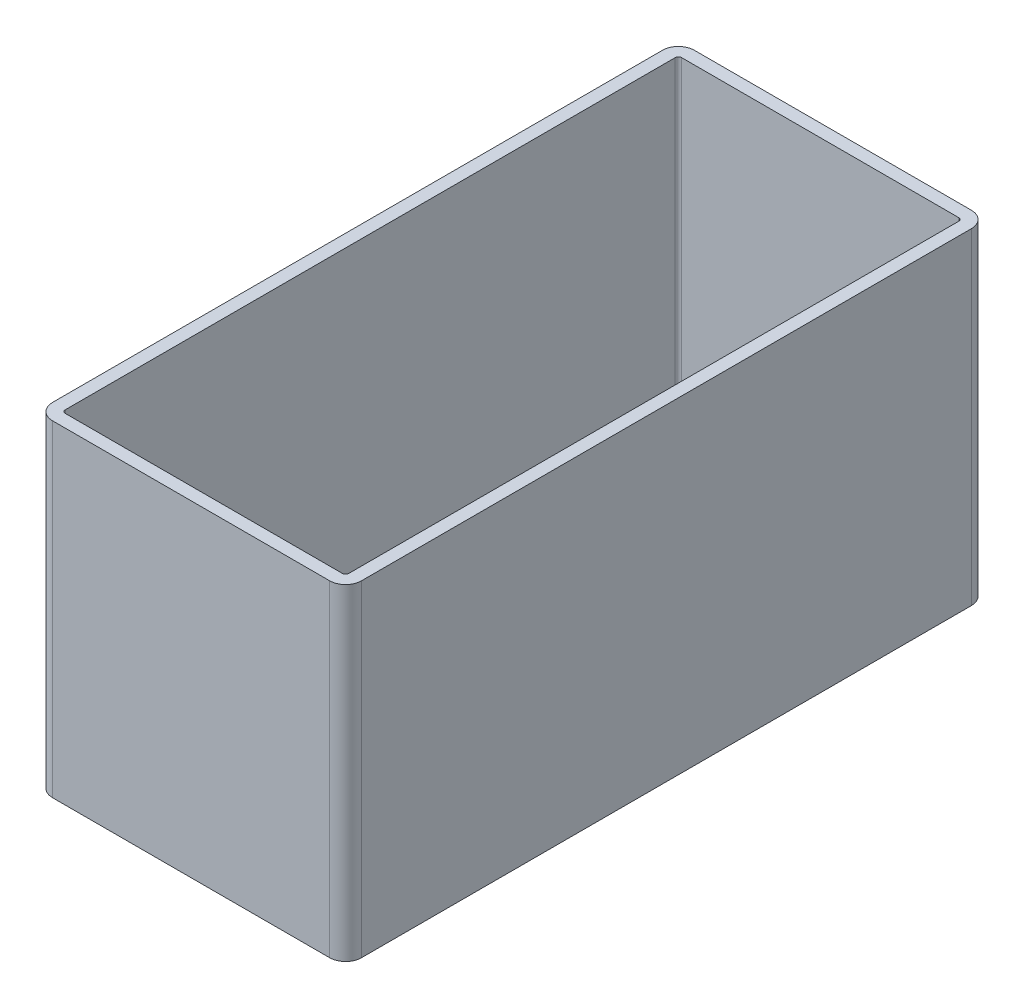
SolidWorks part; units mm, degrees
material "PC High Viscosity"
ref_plane "Front Plane" through (0, 0, 0) normal (0, 0, 1) x (1, 0, 0)
ref_plane "Top Plane" through (0, 0, 0) normal (0, 1, 0) x (1, 0, 0)
ref_plane "Right Plane" through (0, 0, 0) normal (1, 0, 0) x (0, 0, -1)
sketch "BaseS" plane through (0, 0, 0) normal (0, 1, 0) x (1, 0, 0)
  line L1 (-9.7, 20.15) -> (9.7, 20.15)
  line L2 (-9.7, 20.15) -> (-9.7, -20.15)
  line L3 (-9.7, -20.15) -> (9.7, -20.15)
  line L4 (9.7, 20.15) -> (9.7, -20.15)
  line L5 (-9.7, 20.15) -> (9.7, -20.15) construction
  line L6 (-9.7, -20.15) -> (9.7, 20.15) construction
  point P0 (0, 0)
  dimension "D1" = 19.4
  dimension "D2" = 40.3
extrude "BASE" add sketch "BaseS" along normal mid plane 20.5
fillet "BASE F" radius 1 4 edges at (-9.7, 0, -20.15) (9.7, 0, -20.15) (9.7, 0, 20.15) (-9.7, 0, 20.15)
sketch "PocketS" plane through (0, 10.25, 0) normal (0, 1, 0) x (1, 0, 0)
  line L0 (8.7, 19.35) -> (-8.7, 19.35)
  line L1 (-8.9, 19.15) -> (-8.9, -19.15)
  line L2 (-8.7, -19.35) -> (8.7, -19.35)
  line L3 (8.9, -19.15) -> (8.9, 19.15)
  line L4 (8.7, 20.15) -> (-8.7, 20.15)
  line L5 (-9.7, 19.15) -> (-9.7, -19.15)
  line L6 (-8.7, -20.15) -> (8.7, -20.15)
  line L7 (9.7, -19.15) -> (9.7, 19.15)
  line L8 (8.7, 20.15) -> (-8.7, 20.15) construction
  line L9 (-9.7, 19.15) -> (-9.7, -19.15) construction
  line L10 (-8.7, -20.15) -> (8.7, -20.15) construction
  line L11 (9.7, -19.15) -> (9.7, 19.15) construction
  arc A0 (-8.7, 19.35) -> (-8.9, 19.15) centre (-8.7, 19.15) ccw
  arc A1 (-8.9, -19.15) -> (-8.7, -19.35) centre (-8.7, -19.15) ccw
  arc A2 (8.7, -19.35) -> (8.9, -19.15) centre (8.7, -19.15) ccw
  arc A3 (8.9, 19.15) -> (8.7, 19.35) centre (8.7, 19.15) ccw
  arc A4 (-8.7, 20.15) -> (-9.7, 19.15) centre (-8.7, 19.15) ccw
  arc A5 (-9.7, -19.15) -> (-8.7, -20.15) centre (-8.7, -19.15) ccw
  arc A6 (8.7, -20.15) -> (9.7, -19.15) centre (8.7, -19.15) ccw
  arc A7 (9.7, 19.15) -> (8.7, 20.15) centre (8.7, 19.15) ccw
  arc A8 (-8.7, 20.15) -> (-9.7, 19.15) centre (-8.7, 19.15) ccw construction
  arc A9 (-9.7, -19.15) -> (-8.7, -20.15) centre (-8.7, -19.15) ccw construction
  arc A10 (8.7, -20.15) -> (9.7, -19.15) centre (8.7, -19.15) ccw construction
  arc A11 (9.7, 19.15) -> (8.7, 20.15) centre (8.7, 19.15) ccw construction
  dimension "D1" = 0
  dimension "D2" = 0.8
extrude "Cut-Extrude3" cut sketch "PocketS" against normal through all
